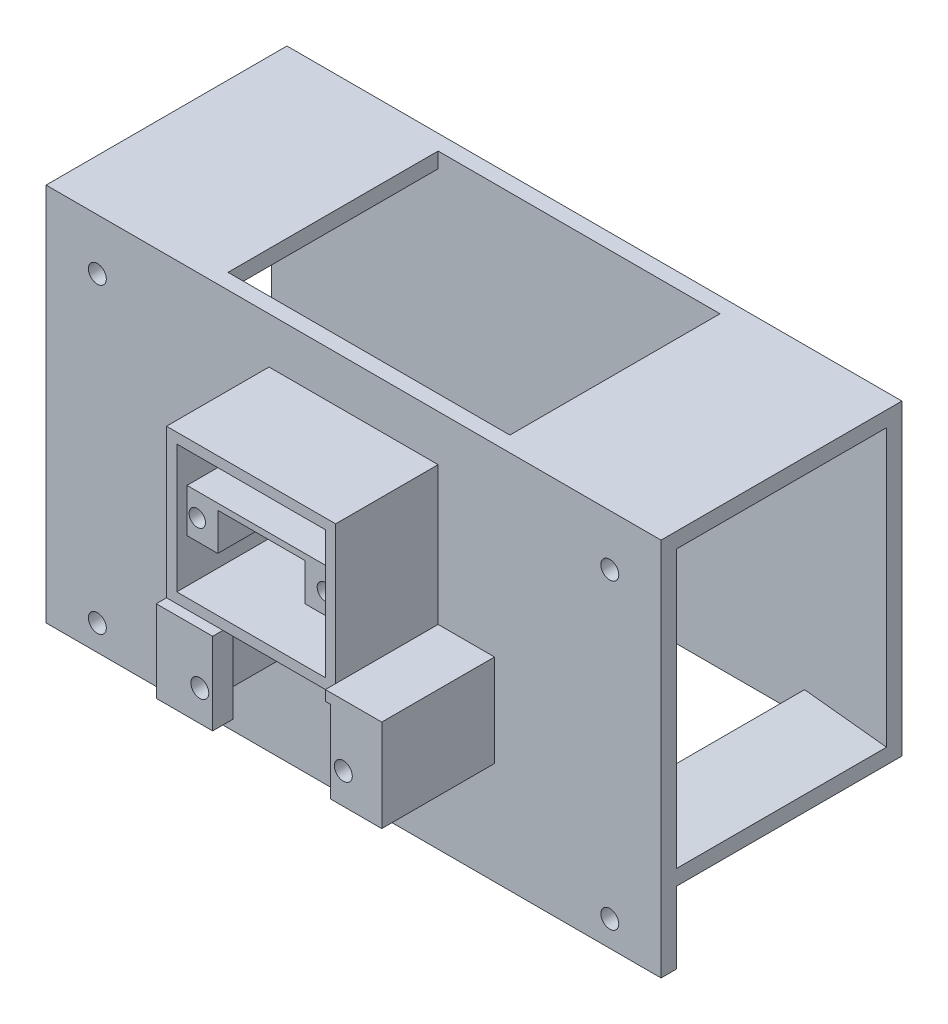
SolidWorks part; units mm, degrees
ref_plane "前视基准面" through (0, 0, 0) normal (0, 0, 1) x (1, 0, 0)
ref_plane "上视基准面" through (0, 0, 0) normal (0, 1, 0) x (1, 0, 0)
ref_plane "右视基准面" through (0, 0, 0) normal (1, 0, 0) x (0, 0, -1)
sketch "草图1" plane through (0, 0, 0) normal (0, 0, -1) x (1, 0, 0)
  line L4 (-60, 30) -> (60, -30) construction
  line L5 (-60, -30) -> (60, -30)
  line L6 (-60, -30) -> (-60, 30)
  line L7 (-60, 30) -> (60, 30)
  line L8 (60, -30) -> (60, 30)
  dimension "D1" = 120
  dimension "D2" = 60
extrude "凸台-拉伸1" add sketch "草图1" along normal blind 47
shell "抽壳2" thickness 3
sketch "草图2" plane through (0, 30, 45) normal (0, -1, 0) x (-1, 0, 0)
  line L0 (0, 92) -> (0, 68.5) construction
  line L1 (-60, 92) -> (60, 92) construction
  line L2 (0, 68.5) -> (-60, 68.5) construction
  line L5 (-60, 92) -> (-60, 45) construction
  line L6 (60, 89) -> (-60, 89) construction
  line L7 (-27.5, 89) -> (27.5, 89)
  line L8 (-27.5, 89) -> (-27.5, 48)
  line L9 (-27.5, 48) -> (27.5, 48)
  line L10 (27.5, 89) -> (27.5, 48)
  line L11 (-27.5, 89) -> (27.5, 48) construction
  line L12 (-27.5, 48) -> (27.5, 89) construction
  point P15 (-60, 68.5)
  dimension "D2" = 55
extrude "切除-拉伸1" cut sketch "草图2" along normal up to surface (3 mm away) up to face at (0, 27, -23.5)
sketch "草图5" plane through (0, -30, 0) normal (0, -1, 0) x (1, 0, 0)
  line L0 (0, 0) -> (0, -23.5) construction
  line L1 (-44, -44) -> (44, -44)
  line L2 (-44, -44) -> (-44, -3)
  line L3 (-44, -3) -> (44, -3)
  line L4 (44, -44) -> (44, -3)
  line L5 (-44, -44) -> (44, -3) construction
  line L6 (-44, -3) -> (44, -44) construction
  line L7 (60, 0) -> (-60, 0) construction
  line L8 (0, -23.5) -> (-60, -23.5) construction
  line L9 (-60, -47) -> (-60, 0) construction
  line L11 (27.5, -3) -> (60, -3) construction
  point P0 (0, -23.5)
  dimension "D1" = 88
extrude "切除-拉伸3" cut sketch "草图5" against normal blind 10
sketch "草图6" plane through (0, 0, 0) normal (0, 0, 1) x (1, 0, 0)
  line L6 (0, 30) -> (0, -18) construction
  line L8 (-60, 30) -> (60, 30) construction
  line L9 (27.5, 27) -> (60, 27) construction
  circle A1 centre (0, -18) radius 2.5
  dimension "D1" = 5
  dimension "D2" = 45
  dimension "D3" = 48
extrude "切除-拉伸4" cut sketch "草图6" against normal through all
sketch "草图8" plane through (0, 0, -44) normal (0, 0, -1) x (-1, 0, 0)
  line L0 (-60, -27) -> (-44, -25.2705)
  line L1 (-44, -25.2705) -> (-44, -30)
  line L2 (-60, -30) -> (60, -30) construction
  line L3 (-44, -30) -> (-60, -30)
  line L4 (-60, -30) -> (-60, -27)
  line L6 (-60, 30) -> (-60, -30) construction
  line L7 (-44, -27) -> (-44, -30) construction
  circle A0 centre (0, -18) radius 1.3759 construction
  circle A1 centre (0, -18) radius 2.5 construction
extrude "凸台-拉伸4" add sketch "草图8" against normal up to surface (41 mm away)
mirror "镜向1" about plane through (0, 0, 0) normal (1, 0, 0) of "凸台-拉伸4"
sketch "草图9" plane through (0, 0, 0) normal (0, 0, 1) x (1, 0, 0)
  line L0 (0, 6.5) -> (0, 30) construction
  line L1 (-8.5, 19) -> (8.5, 19)
  line L2 (-8.5, 19) -> (-8.5, -6)
  line L3 (-8.5, -6) -> (8.5, -6)
  line L4 (8.5, 19) -> (8.5, -6)
  line L5 (-8.5, 19) -> (8.5, -6) construction
  line L6 (-8.5, -6) -> (8.5, 19) construction
  line L7 (-60, 30) -> (60, 30) construction
  point P0 (0, 6.5)
  dimension "D1" = 17
  dimension "D2" = 25
  dimension "D3" = 11
extrude "切除-拉伸5" cut sketch "草图9" against normal up to next
sketch "草图10" plane through (0, 0, 0) normal (0, 0, 1) x (1, 0, 0)
  line L0 (0, 19) -> (0, 6.5) construction
  line L3 (-10.5, -8) -> (10.5, -8)
  line L5 (-16.5, 21) -> (16.5, 21)
  line L6 (-8.5, 19) -> (8.5, 19) construction
  line L11 (8.5, -6) -> (-8.5, -6) construction
  line L12 (-8.5, -6) -> (-8.5, 19) construction
  line L13 (8.5, 19) -> (-8.5, 19) construction
  line L14 (0, 6.5) -> (-8.5, 6.5) construction
  line L15 (-8.5, 19) -> (-8.5, -6) construction
  line L22 (-8.5, 11) -> (14.5, 11)
  line L23 (-8.5, 9.8) -> (8.5, 9.8)
  line L24 (8.5, 9.8) -> (8.5, 2.5)
  line L25 (-8.5, 9.8) -> (-8.5, 2.5)
  line L26 (8.5, 19) -> (8.5, -6) construction
  line L27 (-16.5, 21) -> (-16.5, -8)
  line L28 (-16.5, -8) -> (-10.5, -8)
  line L30 (16.5, 21) -> (16.5, -8)
  line L31 (16.5, -8) -> (10.5, -8)
  line L34 (-14.5, 19) -> (14.5, 19)
  line L35 (-14.5, 19) -> (-14.5, 11)
  line L36 (-14.5, 11) -> (-8.5, 11)
  line L38 (14.5, 19) -> (14.5, 11)
  line L40 (-8.5, 2.5) -> (-14.5, 2.5)
  line L41 (-14.5, 2.5) -> (-14.5, -6)
  line L42 (-14.5, -6) -> (14.5, -6)
  line L43 (8.5, 2.5) -> (14.5, 2.5)
  line L44 (14.5, 2.5) -> (14.5, -6)
  line L45 (-14.5, 11) -> (-14.5, 2.5) construction
  line L48 (-14.5, 6.75) -> (-22.7649, 6.75) construction
  circle A1 centre (-12.5, 6.5) radius 1.6
  circle A3 centre (12.5, 6.5) radius 1.6
  point P0 (0, 6.5)
  point P5 (0, 6.5)
  dimension "D3" = 3.2
  dimension "D4" = 25
  dimension "D2" = 4
  dimension "D5" = 1.2
  dimension "D6" = 4
  dimension "D7" = 2
  dimension "D8" = 2
  dimension "D9" = 2
  dimension "D10" = 2
  dimension "D11" = 8
  dimension "D12" = 25
  dimension "D13" = 4
  dimension "D14" = 29
extrude "凸台-拉伸5" add sketch "草图10" along normal blind 18
sketch "草图13" plane through (0, 0, 18) normal (0, 0, 1) x (1, 0, 0)
  line L1 (-14.5, 19) -> (14.5, 19)
  line L2 (-14.5, 19) -> (-14.5, -6)
  line L3 (-14.5, -6) -> (14.5, -6)
  line L4 (-16.5, -8) -> (16.5, -8)
  line L5 (16.5, -8) -> (16.5, 21)
  line L6 (16.5, 21) -> (-16.5, 21)
  line L7 (-16.5, 21) -> (-16.5, -8)
  line L8 (-16.5, -8) -> (16.5, -8)
  line L9 (16.5, -8) -> (16.5, 21)
  line L10 (16.5, 21) -> (-16.5, 21)
  line L11 (-16.5, 21) -> (-16.5, -8)
  line L12 (14.5, 19) -> (14.5, -6)
  dimension "D1" = 0
extrude "凸台-拉伸6" add sketch "草图13" along normal blind 2
sketch "草图14" plane through (0, 0, 0) normal (0, 0, 1) x (1, 0, 0)
  line L0 (-5.5, -16) -> (17.5, -16) construction
  line L1 (-15.5, -8) -> (-5.5, -8)
  line L2 (-15.5, -8) -> (-15.5, -24)
  line L3 (-15.5, -24) -> (-5.5, -24)
  line L4 (-5.5, -8) -> (-5.5, -24)
  line L5 (17.5, -8) -> (27.5, -8)
  line L6 (17.5, -8) -> (17.5, -24)
  line L7 (17.5, -24) -> (27.5, -24)
  line L8 (27.5, -8) -> (27.5, -24)
  line L9 (-8, -18) -> (0, -18) construction
  line L10 (6, -16) -> (6, -23.5101) construction
  line L11 (-16.5, -8) -> (16.5, -8) construction
  circle A1 centre (-8, -18) radius 1.75
  circle A2 centre (20, -18) radius 1.75
  dimension "D5" = 3.5
  dimension "D1" = 8
  dimension "D2" = 28
  dimension "D3" = 23
  dimension "D4" = 10
  dimension "D6" = 6
extrude "凸台-拉伸7" add sketch "草图14" along normal blind 22
sketch "草图15" plane through (0, 0, 0) normal (0, 0, 1) x (1, 0, 0)
  circle A0 centre (0, -18) radius 10.5
  dimension "D1" = 21
extrude "切除-拉伸7" cut sketch "草图15" along normal blind 12
sketch "草图17" plane through (0, 0, 12) normal (0, 0, -1) x (-1, 0, 0)
  line L5 (5.5, -9.0557) -> (5.5, -24)
  line L6 (5.5, -24) -> (8.6168, -24)
  line L9 (5.5, -9.0557) -> (5.5, -24)
  line L10 (5.5, -24) -> (8.6168, -24)
  arc A3 (8.6168, -24) -> (5.5, -9.0557) centre (0, -18) ccw
  arc A5 (8.6168, -24) -> (5.5, -9.0557) centre (0, -18) ccw
  dimension "D1" = 0
extrude "切除-拉伸8" cut sketch "草图17" against normal offset from surface (6 mm away) 4 up to face at (-10.5, -16, 22)
sketch "草图19" plane through (0, 0, 0) normal (0, 0, 1) x (1, 0, 0)
  line L0 (-15.5, -24) -> (-8.6168, -24) construction
  line L1 (-11, -24) -> (23, -24)
  line L2 (-11, -24) -> (-11, -8)
  line L3 (-11, -8) -> (23, -8)
  line L4 (23, -24) -> (23, -8)
  line L7 (-5.5, -8) -> (16.5, -8) construction
  line L8 (-8, -18) -> (20, -18) construction
  line L9 (6, -18) -> (6, -24) construction
  dimension "D1" = 34
extrude "切除-拉伸9" cut sketch "草图19" along normal up to surface (18 mm away) up to face at (-6.25, -18, 18)
sketch "草图16" plane through (0, 0, 0) normal (0, 0, 1) x (1, 0, 0)
  line L0 (-14.5, -6) -> (14.5, -6) construction
  line L1 (-16.5, -8) -> (-15.5, -8)
  line L2 (-16.5, -8) -> (-16.5, -24)
  line L3 (-16.5, -24) -> (-15.5, -24)
  line L4 (-15.5, -8) -> (-15.5, -24)
  line L5 (16.5, -8) -> (27.5, -8)
  line L6 (16.5, -8) -> (16.5, -6)
  line L7 (16.5, -6) -> (27.5, -6)
  line L8 (27.5, -8) -> (27.5, -6)
  line L10 (27.5, -24) -> (27.5, -8) construction
extrude "凸台-拉伸8" add sketch "草图16" along normal up to surface (22 mm away) up to face at (-10.5, -16, 22)
sketch "草图20" plane through (0, 0, -3) normal (0, 0, -1) x (-1, 0, 0)
  line L1 (-15.5, 9.5) -> (-9.5, 9.5)
  line L2 (-15.5, 9.5) -> (-15.5, 3.5)
  line L3 (-15.5, 3.5) -> (-9.5, 3.5)
  line L4 (-9.5, 9.5) -> (-9.5, 3.5)
  line L5 (-15.5, 9.5) -> (-9.5, 3.5) construction
  line L6 (-15.5, 3.5) -> (-9.5, 9.5) construction
  line L7 (15.5, 9.5) -> (9.5, 9.5)
  line L8 (15.5, 9.5) -> (15.5, 3.5)
  line L9 (15.5, 3.5) -> (9.5, 3.5)
  line L10 (9.5, 9.5) -> (9.5, 3.5)
  line L11 (15.5, 9.5) -> (9.5, 3.5) construction
  line L12 (15.5, 3.5) -> (9.5, 9.5) construction
  circle A4 centre (-12.5, 6.5) radius 1.6 construction
  circle A5 centre (12.5, 6.5) radius 1.6 construction
  point P0 (-12.5, 6.5)
  point P5 (12.5, 6.5)
  dimension "D2" = 6
extrude "切除-拉伸10" cut sketch "草图20" against normal offset from surface (11 mm away) 10 up to face at (14.1, 6.5, 18)
sketch "草图21" plane through (0, -30, 0) normal (0, -1, 0) x (1, 0, 0)
  line L0 (60, -47) -> (60, 0) construction
  line L1 (-60, 0) -> (60, 0)
  line L2 (-60, 0) -> (-60, -3)
  line L3 (-60, -3) -> (60, -3)
  line L4 (60, 0) -> (60, -3)
  line L5 (44, -3) -> (-44, -3) construction
extrude "凸台-拉伸9" add sketch "草图21" along normal blind 14
sketch "草图11" plane through (0, 0, 0) normal (0, 0, -1) x (-1, 0, 0)
  line L0 (0, 30) -> (0, -30) construction
  line L1 (60, 30) -> (-60, 30) construction
  line L2 (-60, -30) -> (60, -30) construction
  line L3 (60, -44) -> (-60, -44) construction
  circle A0 centre (-50, 20) radius 1.75
  circle A1 centre (50, 20) radius 1.75
  circle A2 centre (-50, -39) radius 1.75
  circle A3 centre (50, -39) radius 1.75
  dimension "D1" = 3.5
  dimension "D2" = 100
  dimension "D3" = 10
  dimension "D4" = 5
  dimension "D5" = 59
extrude "切除-拉伸6" cut sketch "草图11" along normal through all
